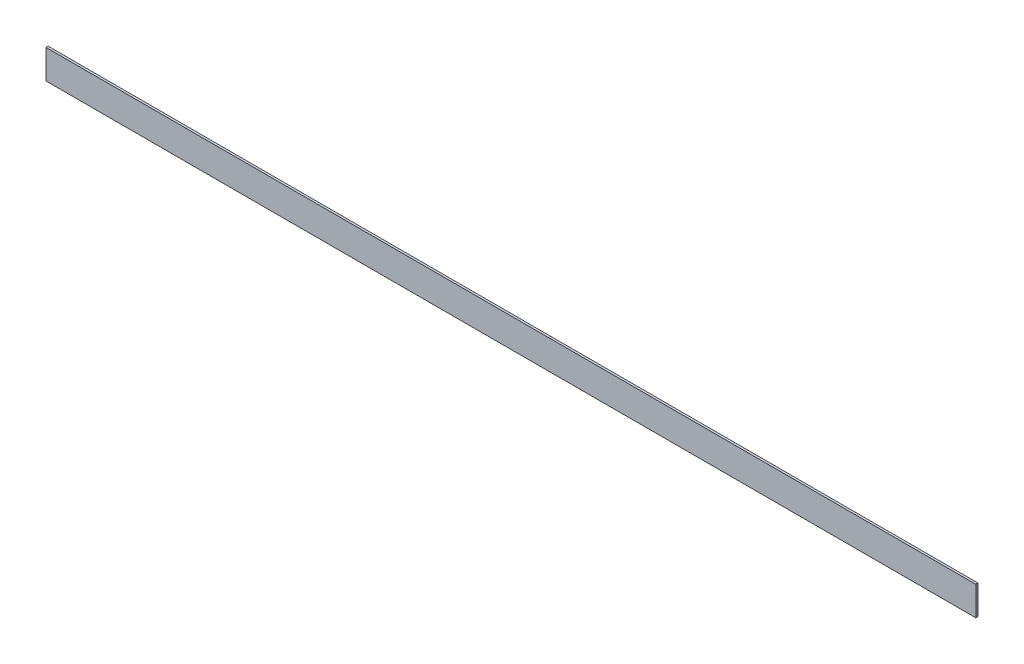
SolidWorks part; units mm, degrees
ref_plane "Front Plane" through (0, 0, 0) normal (0, 0, 1) x (1, 0, 0)
ref_plane "Top Plane" through (0, 0, 0) normal (0, 1, 0) x (1, 0, 0)
ref_plane "Right Plane" through (0, 0, 0) normal (1, 0, 0) x (0, 0, -1)
other "Configuration Table"
sketch "Sketch1" plane through (0, 0, 0) normal (0, 0, 1) x (1, 0, 0)
  line L1 (30, 1950) -> (670, 1950)
  line L2 (30, 1950) -> (30, 1970)
  line L3 (30, 1970) -> (670, 1970)
  line L4 (670, 1950) -> (670, 1970)
extrude "PACK_panel_ust_pay_1" add sketch "Sketch1" along normal blind 1.5 from offset 38.5 separate body
